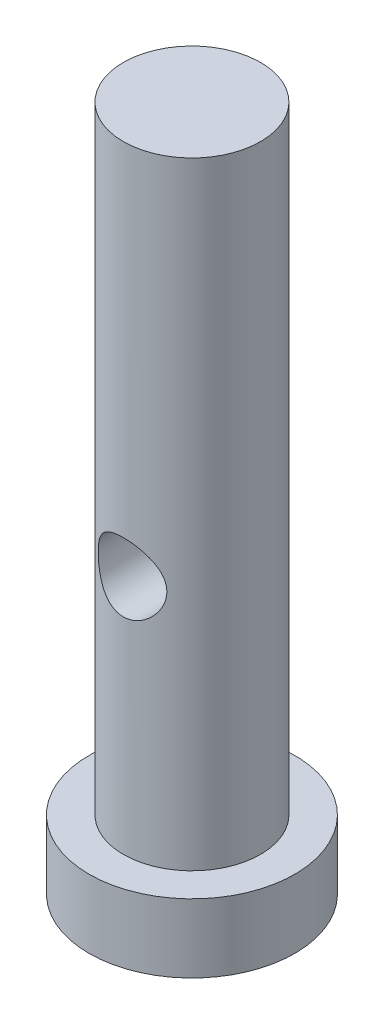
SolidWorks part; units mm, degrees
ref_plane "Front Plane" through (0, 0, 0) normal (0, 0, 1) x (1, 0, 0)
ref_plane "Top Plane" through (0, 0, 0) normal (0, 1, 0) x (1, 0, 0)
ref_plane "Right Plane" through (0, 0, 0) normal (1, 0, 0) x (0, 0, -1)
sketch "Sketch1" plane through (0, 0, 0) normal (0, 1, 0) x (1, 0, 0)
  circle A0 centre (0, 0) radius 7.5
extrude "Boss-Extrude1" add sketch "Sketch1" along normal blind 5
sketch "Sketch2" plane through (0, 5, 0) normal (0, 1, 0) x (1, 0, 0)
  circle A0 centre (0, 0) radius 5
extrude "Boss-Extrude2" add sketch "Sketch2" along normal blind 45
sketch "Sketch3" plane through (0, 0, 0) normal (0, 0, 1) x (1, 0, 0)
  line L0 (0, 5) -> (0, 22.5) construction
  line L1 (7.5, 5) -> (-7.5, 5) construction
  circle A0 centre (0, 22.5) radius 2.5
extrude "Cut-Extrude1" cut sketch "Sketch3" against normal blind 28 and the other way blind 25
